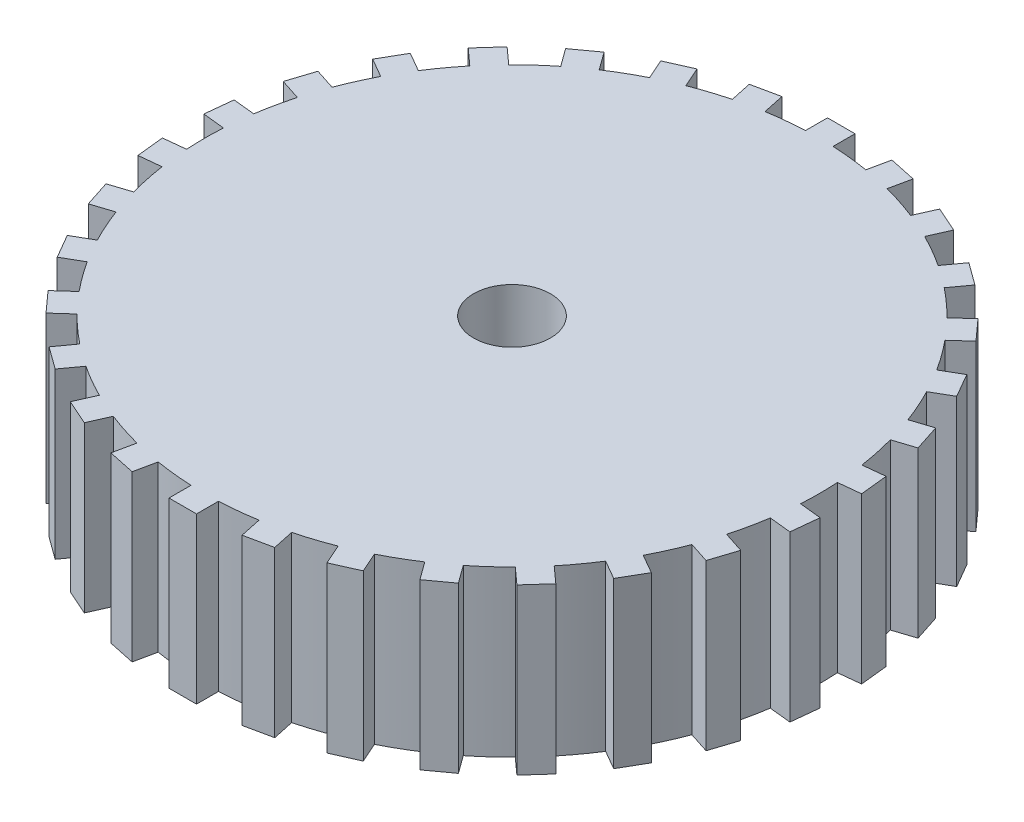
SolidWorks part; units mm, degrees
ref_plane "Alzado" through (0, 0, 0) normal (0, 0, 1) x (1, 0, 0)
ref_plane "Planta" through (0, 0, 0) normal (0, 1, 0) x (1, 0, 0)
ref_plane "Vista lateral" through (0, 0, 0) normal (1, 0, 0) x (0, 0, -1)
sketch "Croquis2" plane through (0, 0, 0) normal (0, 1, 0) x (1, 0, 0)
  line L3 (-1.2536, 27.9719) -> (-1.2536, 29.9738)
  line L4 (-1.2536, 29.9738) -> (1.2536, 29.9738)
  line L5 (1.2536, 27.9719) -> (1.2536, 29.9738)
  line L6 (7.0419, 27.1) -> (7.4581, 29.0582)
  line L7 (5.0057, 29.5794) -> (7.4581, 29.0582)
  line L8 (4.5895, 27.6213) -> (5.0057, 29.5794)
  line L10 (12.5225, 25.0437) -> (13.3367, 26.8725)
  line L11 (11.0462, 27.8923) -> (13.3367, 26.8725)
  line L12 (10.232, 26.0635) -> (11.0462, 27.8923)
  line L14 (17.4557, 21.8929) -> (18.6324, 23.5124)
  line L15 (16.6039, 24.9862) -> (18.6324, 23.5124)
  line L16 (15.4273, 23.3666) -> (16.6039, 24.9862)
  line L18 (21.626, 17.7852) -> (23.1137, 19.1248)
  line L19 (21.436, 20.988) -> (23.1137, 19.1248)
  line L20 (19.9483, 19.6485) -> (21.436, 20.988)
  line L22 (24.8512, 12.9003) -> (26.5849, 13.9012)
  line L23 (25.3313, 16.0726) -> (26.5849, 13.9012)
  line L24 (23.5976, 15.0716) -> (25.3313, 16.0726)
  line L26 (26.9903, 7.4515) -> (28.8942, 8.0701)
  line L27 (28.1194, 10.4547) -> (28.8942, 8.0701)
  line L28 (26.2155, 9.8361) -> (28.1194, 10.4547)
  line L30 (27.9497, 1.6771) -> (29.9406, 1.8863)
  line L31 (29.6786, 4.3799) -> (29.9406, 1.8863)
  line L32 (27.6876, 4.1706) -> (29.6786, 4.3799)
  line L34 (27.6876, -4.1706) -> (29.6786, -4.3799)
  line L35 (29.9406, -1.8863) -> (29.6786, -4.3799)
  line L36 (27.9497, -1.6771) -> (29.9406, -1.8863)
  line L38 (26.2155, -9.8361) -> (28.1194, -10.4547)
  line L39 (28.8942, -8.0701) -> (28.1194, -10.4547)
  line L40 (26.9903, -7.4515) -> (28.8942, -8.0701)
  line L42 (23.5976, -15.0716) -> (25.3313, -16.0726)
  line L43 (26.5849, -13.9012) -> (25.3313, -16.0726)
  line L44 (24.8512, -12.9003) -> (26.5849, -13.9012)
  line L46 (19.9483, -19.6485) -> (21.436, -20.988)
  line L47 (23.1137, -19.1248) -> (21.436, -20.988)
  line L48 (21.626, -17.7852) -> (23.1137, -19.1248)
  line L50 (15.4273, -23.3666) -> (16.6039, -24.9862)
  line L51 (18.6324, -23.5124) -> (16.6039, -24.9862)
  line L52 (17.4557, -21.8929) -> (18.6324, -23.5124)
  line L54 (10.232, -26.0635) -> (11.0462, -27.8923)
  line L55 (13.3367, -26.8725) -> (11.0462, -27.8923)
  line L56 (12.5225, -25.0437) -> (13.3367, -26.8725)
  line L58 (4.5895, -27.6213) -> (5.0057, -29.5794)
  line L59 (7.4581, -29.0582) -> (5.0057, -29.5794)
  line L60 (7.0419, -27.1) -> (7.4581, -29.0582)
  line L62 (-1.2536, -27.9719) -> (-1.2536, -29.9738)
  line L63 (1.2536, -29.9738) -> (-1.2536, -29.9738)
  line L64 (1.2536, -27.9719) -> (1.2536, -29.9738)
  line L66 (-7.0419, -27.1) -> (-7.4581, -29.0582)
  line L67 (-5.0057, -29.5794) -> (-7.4581, -29.0582)
  line L68 (-4.5895, -27.6213) -> (-5.0057, -29.5794)
  line L70 (-12.5225, -25.0437) -> (-13.3367, -26.8725)
  line L71 (-11.0462, -27.8923) -> (-13.3367, -26.8725)
  line L72 (-10.232, -26.0635) -> (-11.0462, -27.8923)
  line L74 (-17.4557, -21.8929) -> (-18.6324, -23.5124)
  line L75 (-16.6039, -24.9862) -> (-18.6324, -23.5124)
  line L76 (-15.4273, -23.3666) -> (-16.6039, -24.9862)
  line L78 (-21.626, -17.7852) -> (-23.1137, -19.1248)
  line L79 (-21.436, -20.988) -> (-23.1137, -19.1248)
  line L80 (-19.9483, -19.6485) -> (-21.436, -20.988)
  line L82 (-24.8512, -12.9003) -> (-26.5849, -13.9012)
  line L83 (-25.3313, -16.0726) -> (-26.5849, -13.9012)
  line L84 (-23.5976, -15.0716) -> (-25.3313, -16.0726)
  line L86 (-26.9903, -7.4515) -> (-28.8942, -8.0701)
  line L87 (-28.1194, -10.4547) -> (-28.8942, -8.0701)
  line L88 (-26.2155, -9.8361) -> (-28.1194, -10.4547)
  line L90 (-27.9497, -1.6771) -> (-29.9406, -1.8863)
  line L91 (-29.6786, -4.3799) -> (-29.9406, -1.8863)
  line L92 (-27.6876, -4.1706) -> (-29.6786, -4.3799)
  line L94 (-27.6876, 4.1706) -> (-29.6786, 4.3799)
  line L95 (-29.9406, 1.8863) -> (-29.6786, 4.3799)
  line L96 (-27.9497, 1.6771) -> (-29.9406, 1.8863)
  line L98 (-26.2155, 9.8361) -> (-28.1194, 10.4547)
  line L99 (-28.8942, 8.0701) -> (-28.1194, 10.4547)
  line L100 (-26.9903, 7.4515) -> (-28.8942, 8.0701)
  line L102 (-23.5976, 15.0716) -> (-25.3313, 16.0726)
  line L103 (-26.5849, 13.9012) -> (-25.3313, 16.0726)
  line L104 (-24.8512, 12.9003) -> (-26.5849, 13.9012)
  line L106 (-19.9483, 19.6485) -> (-21.436, 20.988)
  line L107 (-23.1137, 19.1248) -> (-21.436, 20.988)
  line L108 (-21.626, 17.7852) -> (-23.1137, 19.1248)
  line L110 (-15.4273, 23.3666) -> (-16.6039, 24.9862)
  line L111 (-18.6324, 23.5124) -> (-16.6039, 24.9862)
  line L112 (-17.4557, 21.8929) -> (-18.6324, 23.5124)
  line L114 (-10.232, 26.0635) -> (-11.0462, 27.8923)
  line L115 (-13.3367, 26.8725) -> (-11.0462, 27.8923)
  line L116 (-12.5225, 25.0437) -> (-13.3367, 26.8725)
  line L118 (-4.5895, 27.6213) -> (-5.0057, 29.5794)
  line L119 (-7.4581, 29.0582) -> (-5.0057, 29.5794)
  line L120 (-7.0419, 27.1) -> (-7.4581, 29.0582)
  arc A0 (-17.4557, 21.8929) -> (-19.9483, 19.6485) centre (0, 0) ccw
  arc A1 (-16.6039, 24.9862) -> (-18.6324, 23.5124) centre (0, 0) ccw
  arc A2 (-11.0462, 27.8923) -> (-13.3367, 26.8725) centre (0, 0) ccw
  arc A3 (-5.0057, 29.5794) -> (-7.4581, 29.0582) centre (0, 0) ccw
  arc A4 (1.2536, 29.9738) -> (-1.2536, 29.9738) centre (0, 0) ccw
  arc A5 (7.4581, 29.0582) -> (5.0057, 29.5794) centre (0, 0) ccw
  arc A6 (13.3367, 26.8725) -> (11.0462, 27.8923) centre (0, 0) ccw
  arc A7 (18.6324, 23.5124) -> (16.6039, 24.9862) centre (0, 0) ccw
  arc A8 (23.1137, 19.1248) -> (21.436, 20.988) centre (0, 0) ccw
  arc A9 (26.5849, 13.9012) -> (25.3313, 16.0726) centre (0, 0) ccw
  arc A10 (28.8942, 8.0701) -> (28.1194, 10.4547) centre (0, 0) ccw
  arc A11 (29.9406, 1.8863) -> (29.6786, 4.3799) centre (0, 0) ccw
  arc A12 (29.6786, -4.3799) -> (29.9406, -1.8863) centre (0, 0) ccw
  arc A13 (28.1194, -10.4547) -> (28.8942, -8.0701) centre (0, 0) ccw
  arc A14 (25.3313, -16.0726) -> (26.5849, -13.9012) centre (0, 0) ccw
  arc A15 (21.436, -20.988) -> (23.1137, -19.1248) centre (0, 0) ccw
  arc A16 (16.6039, -24.9862) -> (18.6324, -23.5124) centre (0, 0) ccw
  arc A17 (11.0462, -27.8923) -> (13.3367, -26.8725) centre (0, 0) ccw
  arc A18 (5.0057, -29.5794) -> (7.4581, -29.0582) centre (0, 0) ccw
  arc A19 (-1.2536, -29.9738) -> (1.2536, -29.9738) centre (0, 0) ccw
  arc A20 (-7.4581, -29.0582) -> (-5.0057, -29.5794) centre (0, 0) ccw
  arc A21 (-13.3367, -26.8725) -> (-11.0462, -27.8923) centre (0, 0) ccw
  arc A22 (-18.6324, -23.5124) -> (-16.6039, -24.9862) centre (0, 0) ccw
  arc A23 (-23.1137, -19.1248) -> (-21.436, -20.988) centre (0, 0) ccw
  arc A24 (-26.5849, -13.9012) -> (-25.3313, -16.0726) centre (0, 0) ccw
  arc A25 (-28.8942, -8.0701) -> (-28.1194, -10.4547) centre (0, 0) ccw
  arc A26 (-29.9406, -1.8863) -> (-29.6786, -4.3799) centre (0, 0) ccw
  arc A27 (-29.6786, 4.3799) -> (-29.9406, 1.8863) centre (0, 0) ccw
  arc A28 (-28.1194, 10.4547) -> (-28.8942, 8.0701) centre (0, 0) ccw
  arc A29 (-25.3313, 16.0726) -> (-26.5849, 13.9012) centre (0, 0) ccw
  arc A30 (-21.436, 20.988) -> (-23.1137, 19.1248) centre (0, 0) ccw
  circle A31 centre (0, 0) radius 27
  arc A32 (-12.5225, 25.0437) -> (-15.4273, 23.3666) centre (0, 0) ccw
  arc A33 (-7.0419, 27.1) -> (-10.232, 26.0635) centre (0, 0) ccw
  arc A34 (-1.2536, 27.9719) -> (-4.5895, 27.6213) centre (0, 0) ccw
  arc A35 (4.5895, 27.6213) -> (1.2536, 27.9719) centre (0, 0) ccw
  arc A36 (10.232, 26.0635) -> (7.0419, 27.1) centre (0, 0) ccw
  arc A37 (15.4273, 23.3666) -> (12.5225, 25.0437) centre (0, 0) ccw
  arc A38 (19.9483, 19.6485) -> (17.4557, 21.8929) centre (0, 0) ccw
  arc A39 (23.5976, 15.0716) -> (21.626, 17.7852) centre (0, 0) ccw
  arc A40 (26.2155, 9.8361) -> (24.8512, 12.9003) centre (0, 0) ccw
  arc A41 (27.6876, 4.1706) -> (26.9903, 7.4515) centre (0, 0) ccw
  arc A42 (27.9497, -1.6771) -> (27.9497, 1.6771) centre (0, 0) ccw
  arc A43 (26.9903, -7.4515) -> (27.6876, -4.1706) centre (0, 0) ccw
  arc A44 (24.8512, -12.9003) -> (26.2155, -9.8361) centre (0, 0) ccw
  arc A45 (21.626, -17.7852) -> (23.5976, -15.0716) centre (0, 0) ccw
  arc A46 (17.4557, -21.8929) -> (19.9483, -19.6485) centre (0, 0) ccw
  arc A47 (12.5225, -25.0437) -> (15.4273, -23.3666) centre (0, 0) ccw
  arc A48 (7.0419, -27.1) -> (10.232, -26.0635) centre (0, 0) ccw
  arc A49 (1.2536, -27.9719) -> (4.5895, -27.6213) centre (0, 0) ccw
  arc A50 (-4.5895, -27.6213) -> (-1.2536, -27.9719) centre (0, 0) ccw
  arc A51 (-10.232, -26.0635) -> (-7.0419, -27.1) centre (0, 0) ccw
  arc A52 (-15.4273, -23.3666) -> (-12.5225, -25.0437) centre (0, 0) ccw
  arc A53 (-19.9483, -19.6485) -> (-17.4557, -21.8929) centre (0, 0) ccw
  arc A54 (-23.5976, -15.0716) -> (-21.626, -17.7852) centre (0, 0) ccw
  arc A55 (-26.2155, -9.8361) -> (-24.8512, -12.9003) centre (0, 0) ccw
  arc A56 (-27.6876, -4.1706) -> (-26.9903, -7.4515) centre (0, 0) ccw
  arc A57 (-27.9497, 1.6771) -> (-27.9497, -1.6771) centre (0, 0) ccw
  arc A58 (-26.9903, 7.4515) -> (-27.6876, 4.1706) centre (0, 0) ccw
  arc A59 (-24.8512, 12.9003) -> (-26.2155, 9.8361) centre (0, 0) ccw
  arc A60 (-21.626, 17.7852) -> (-23.5976, 15.0716) centre (0, 0) ccw
  point P126 (0, 0)
  dimension "D1" = 30
extrude "Saliente-Extruir1" add sketch "Croquis2" along normal blind 15 contours L108 A60 L102 L103 L104 A59 L98 L99 L100 A58 L94 L95 L96 A57 L90 L91 L92 A56 L86 L87 L88 A55 L82 L83 L84 A54 L78 L79 L80 A53 L74 L75 L76 A52 L70 L71 L72 A51 L66 L67 L68 A50 L62 L63 L64 A49 L58 L59 L60 A48 L54 | A31
sketch "Croquis3" plane through (0, 0, 0) normal (0, -1, 0) x (1, 0, 0)
  circle A0 centre (0, 0) radius 3.5
  circle A1 centre (0, 0) radius 18
extrude "Saliente-Extruir2" add sketch "Croquis3" along normal blind 0.5 contours A1
sketch "Croquis4" plane through (0, -0.5, 0) normal (0, -1, 0) x (1, 0, 0)
  circle A0 centre (0, 0) radius 3.5
extrude "Cortar-Extruir1" cut sketch "Croquis4" against normal blind 24.5
sketch "Croquis5" plane through (0, -0.5, 0) normal (0, -1, 0) x (-1, 0, 0)
  circle A0 centre (0, 0) radius 10
extrude "Cortar-Extruir2" cut sketch "Croquis5" against normal blind 0.5
sketch "Croquis6" plane through (0, 0, 0) normal (0, -1, 0) x (1, 0, 0)
  circle A0 centre (0, 0) radius 26.6765
  circle A1 centre (0, 0) radius 18
extrude "Cortar-Extruir3" cut sketch "Croquis6" against normal blind 0.3 contours A0 | A1
